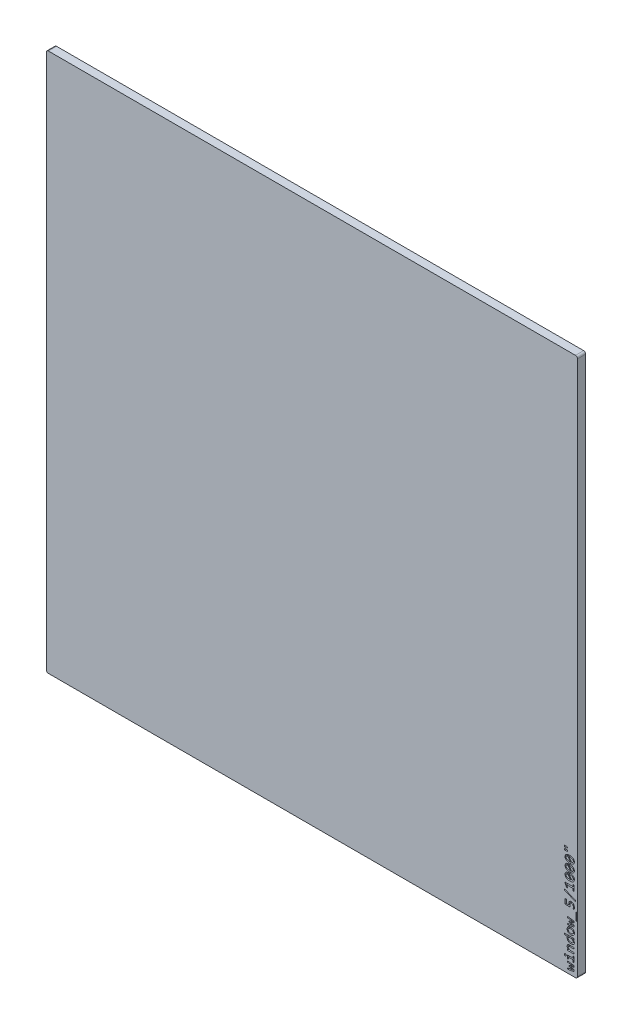
SolidWorks part; units mm, degrees
material "Acrylic (Medium-high impact)"
ref_plane "Front Plane" through (0, 0, 0) normal (0, 0, 1) x (1, 0, 0)
ref_plane "Top Plane" through (0, 0, 0) normal (0, 1, 0) x (1, 0, 0)
ref_plane "Right Plane" through (0, 0, 0) normal (1, 0, 0) x (0, 0, -1)
sketch "Sketch1" plane through (0, 0, 0) normal (0, 0, 1) x (1, 0, 0)
  line L0 (0, 209.55) -> (206.375, 0) construction
  line L1 (0, 0) -> (206.375, 0) construction
  line L2 (0, 0) -> (0, 209.55) construction
  line L3 (0, 209.55) -> (206.375, 209.55) construction
  line L4 (206.375, 0) -> (206.375, 209.55) construction
  line L6 (0.0635, 0.127) -> (206.3115, 0.127)
  line L7 (0.0635, 0.127) -> (0.0635, 209.423)
  line L8 (0.0635, 209.423) -> (206.3115, 209.423)
  line L9 (206.3115, 0.127) -> (206.3115, 209.423)
  line L10 (0.0635, 0.127) -> (206.3115, 209.423) construction
  line L11 (0.0635, 209.423) -> (206.3115, 0.127) construction
  point P5 (103.1875, 104.775)
  dimension "D1" = 209.55
  dimension "D2" = 206.375
  dimension "D3" = 0.127
  dimension "D4" = 0.127
extrude "Boss-Extrude1" add sketch "Sketch1" along normal blind 3.175
fillet "Fillet1" radius 0.7937 4 edges at (0.0635, 0.127, 1.5875) (206.3115, 0.127, 1.5875) (206.3115, 209.423, 1.5875) (0.0635, 209.423, 1.5875)
sketch "Sketch2" plane through (0, 0, 3.175) normal (0, 0, 1) x (1, 0, 0)
  line L0 (205.0415, 209.423) -> (205.0415, 1.397) construction
  line L3 (206.3115, 0.9207) -> (206.3115, 208.6292) construction
  line L4 (205.5177, 209.423) -> (0.8573, 209.423) construction
  line L5 (0.8573, 0.127) -> (205.5177, 0.127) construction
  text T0 "window_5/1000\"" font "Consolas" height 3.5
  point P2 (203.7715, 200.2002)
  point P3 (203.7715, 207.0709)
  point P4 (205.0415, 4.0078)
  point P9 (203.7715, 209.423)
  point P10 (0, 0)
  dimension "D1" = 1.27
  dimension "D2" = 1.27
extrude "Cut-Extrude1" cut sketch "Sketch2" against normal blind 1.27
